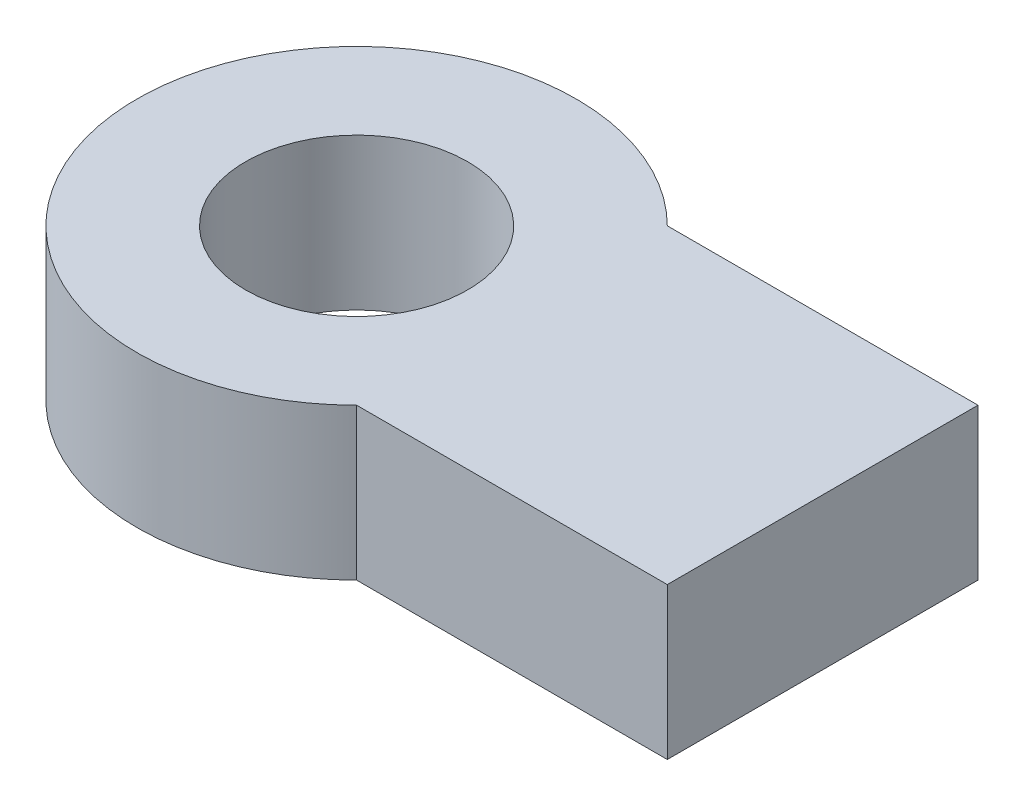
SolidWorks part; units mm, degrees
ref_plane "前视基准面" through (0, 0, 0) normal (0, 0, 1) x (1, 0, 0)
ref_plane "上视基准面" through (0, 0, 0) normal (0, 1, 0) x (1, 0, 0)
ref_plane "右视基准面" through (0, 0, 0) normal (1, 0, 0) x (0, 0, -1)
sketch "草图2" plane through (0, 0, 0) normal (0, 1, 0) x (1, 0, 0)
  line L4 (0, 0) -> (2.175, 0) construction
  line L5 (0, 0) -> (0, 2.175) construction
  line L6 (0, 2.175) -> (2.175, 0) construction
  line L7 (0, 0) -> (1.0875, 1.0875) construction
  line L8 (1.0875, 1.0875) -> (1.538, 1.538) construction
  line L9 (1.538, 1.538) -> (4.6139, 1.538)
  line L11 (4.6139, 1.538) -> (4.6139, -1.538)
  line L12 (1.538, -1.538) -> (4.6139, -1.538)
  circle A2 centre (0, 0) radius 1.1
  arc A3 (1.538, 1.538) -> (1.538, -1.538) centre (0, 0) ccw
  point P8 (0, 0)
  dimension "D1" = 2.2
  dimension "D2" = 4.35
extrude "凸台-拉伸1" add sketch "草图2" along normal blind 1.5
